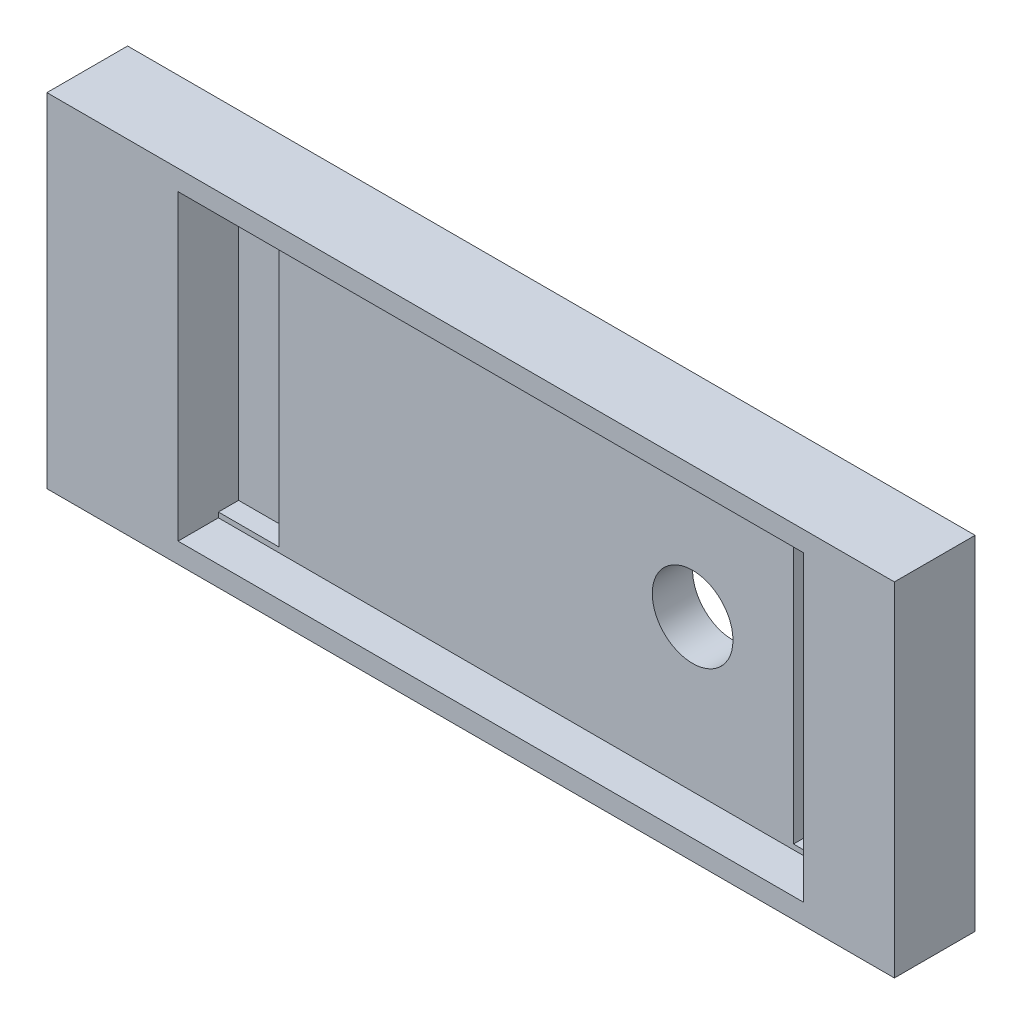
SolidWorks part; units mm, degrees
ref_plane "前视基准面" through (0, 0, 0) normal (0, 0, 1) x (1, 0, 0)
ref_plane "上视基准面" through (0, 0, 0) normal (0, 1, 0) x (1, 0, 0)
ref_plane "右视基准面" through (0, 0, 0) normal (1, 0, 0) x (0, 0, -1)
sketch "草图1" plane through (0, 0, 0) normal (0, 0, 1) x (1, 0, 0)
  line L13 (-30, 8.5) -> (-30, -8.5)
  line L16 (-30, -8.5) -> (12, -8.5)
  line L17 (12, -8.5) -> (12, 0)
  line L20 (12, 0) -> (12, 8.5)
  line L21 (12, 8.5) -> (-30, 8.5)
  circle A1 centre (0, 0) radius 2
  point P3 (11, -8)
  point P9 (11, -37.3394)
  point P10 (-31, 9.618)
  point P11 (-31, -8)
extrude "凸台-拉伸1" add sketch "草图1" along normal blind 2
sketch "草图3" plane through (0, 0, 2) normal (0, 0, 1) x (1, 0, 0)
  line L0 (-20.5, 7.25) -> (-23.5, 7.25)
  line L1 (7.5, 0) -> (7.5, 7.25)
  line L5 (7.5, -7.25) -> (7.5, 0)
  line L6 (7.5, 7.25) -> (5, 7.25)
  line L7 (7.5, 7.25) -> (7.5, -7.25)
  line L8 (7.5, -7.25) -> (5, -7.25)
  line L9 (5, 7.25) -> (5, -7.25)
  line L10 (-23.5, 7.25) -> (-20.5, 7.25)
  line L12 (-23.5, -7.25) -> (-20.5, -7.25)
  line L13 (-20.5, 7.25) -> (-20.5, -7.25)
  line L14 (-23.5, 7.25) -> (-23.5, -7.25)
extrude "切除-拉伸1" cut sketch "草图3" against normal blind 1
sketch "草图4" plane through (0, 0, 2) normal (0, 0, 1) x (1, 0, 0)
  line L0 (11, 7.5) -> (-29, 7.5)
  line L1 (-29, 7.5) -> (-29, -7.5)
  line L2 (-29, -7.5) -> (11, -7.5)
  line L3 (11, -7.5) -> (11, 7.5)
  line L4 (12, -8.5) -> (12, 8.5)
  line L5 (12, 8.5) -> (-30, 8.5)
  line L6 (-30, 8.5) -> (-30, -8.5)
  line L7 (-30, -8.5) -> (12, -8.5)
  line L8 (12, -8.5) -> (12, 8.5)
  line L9 (12, 8.5) -> (-30, 8.5)
  line L10 (-30, 8.5) -> (-30, -8.5)
  line L11 (-30, -8.5) -> (12, -8.5)
  dimension "D1" = 0
  dimension "D2" = 1
extrude "凸台-拉伸2" add sketch "草图4" along normal blind 1
sketch "草图6" plane through (0, 0, 2) normal (0, 0, 1) x (1, 0, 0)
  line L0 (11, 7.5) -> (-29, 7.5) construction
  line L1 (-29, -7.5) -> (-23.5, -7.5)
  line L2 (-29, -7.5) -> (-29, 7.5)
  line L3 (-29, 7.5) -> (-23.5, 7.5)
  line L4 (-23.5, -7.5) -> (-23.5, 7.5)
  line L5 (-29, -7.5) -> (11, -7.5) construction
  line L6 (11, 7.5) -> (7.5, 7.5)
  line L7 (11, 7.5) -> (11, -7.5)
  line L8 (11, -7.5) -> (7.5, -7.5)
  line L9 (7.5, 7.5) -> (7.5, -7.5)
extrude "凸台-拉伸4" add sketch "草图6" along normal blind 1
sketch "草图7" plane through (0, 0, 3) normal (0, 0, 1) x (1, 0, 0)
  line L0 (7.5, 7.5) -> (7.5, -7.5)
  line L1 (-23.5, 7.5) -> (7.5, 7.5)
  line L2 (-23.5, 7.5) -> (-23.5, -7.5)
  line L3 (-23.5, -7.5) -> (7.5, -7.5)
  line L4 (-30, -8.5) -> (12, -8.5)
  line L5 (12, -8.5) -> (12, 8.5)
  line L6 (12, 8.5) -> (-30, 8.5)
  line L7 (-30, 8.5) -> (-30, -8.5)
  line L8 (-30, -8.5) -> (12, -8.5)
  line L9 (12, -8.5) -> (12, 8.5)
  line L10 (12, 8.5) -> (-30, 8.5)
  line L11 (-30, 8.5) -> (-30, -8.5)
  dimension "D1" = 0
extrude "凸台-拉伸5" add sketch "草图7" along normal blind 1
